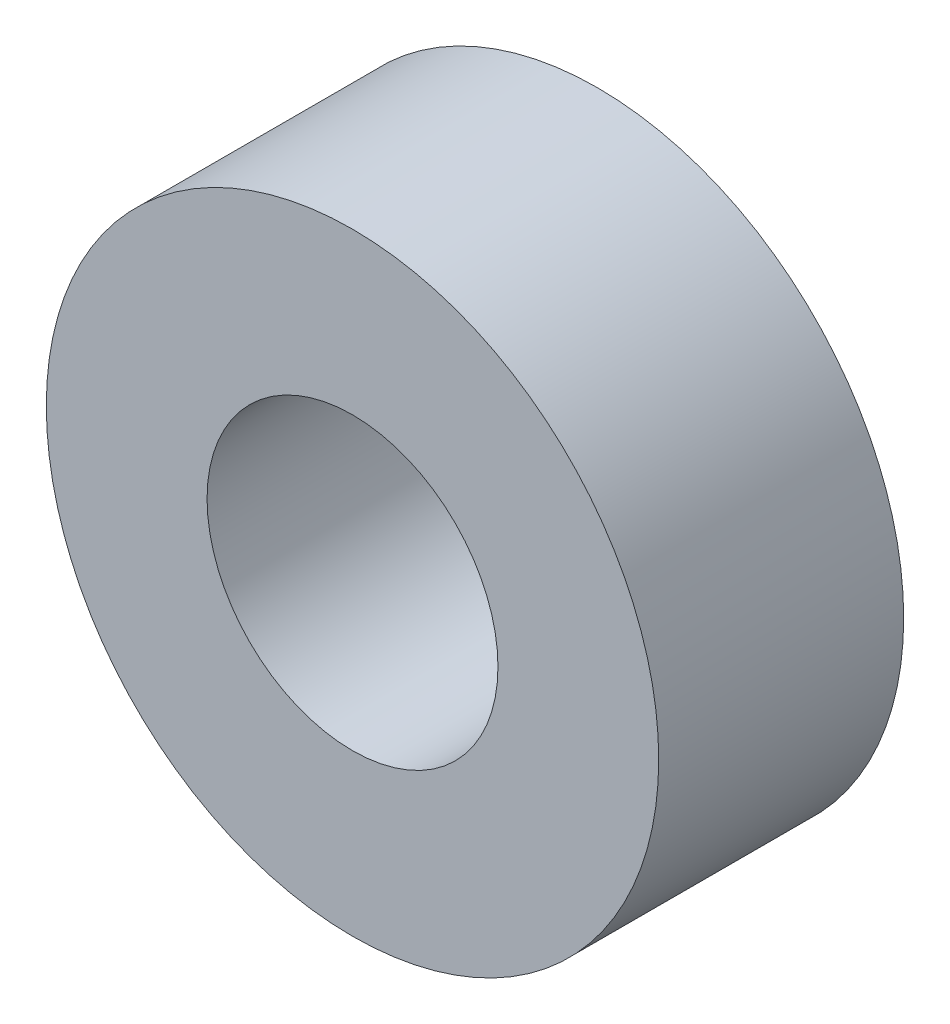
SolidWorks part; units mm, degrees
ref_plane "Front Plane" through (0, 0, 0) normal (0, 0, 1) x (1, 0, 0)
ref_plane "Top Plane" through (0, 0, 0) normal (0, 1, 0) x (1, 0, 0)
ref_plane "Right Plane" through (0, 0, 0) normal (1, 0, 0) x (0, 0, -1)
sketch "Sketch1" plane through (0, 0, 0) normal (0, 0, 1) x (1, 0, 0)
  circle A0 centre (0, 0) radius 4.75
  circle A1 centre (0, 0) radius 10
  point P4 (0, -10)
  dimension "D1" = 9.5
  dimension "D2" = 20
extrude "Boss-Extrude1" add sketch "Sketch1" along normal blind 8
ref_plane "Plane1" through (0, 0, 4) normal (0, 0, 1) x (1, 0, 0)
sketch "Sketch2" plane through (0, 0, 4) normal (0, 0, 1) x (1, 0, 0)
  circle A0 centre (0, 0) radius 5
  circle A1 centre (0, 0) radius 10
